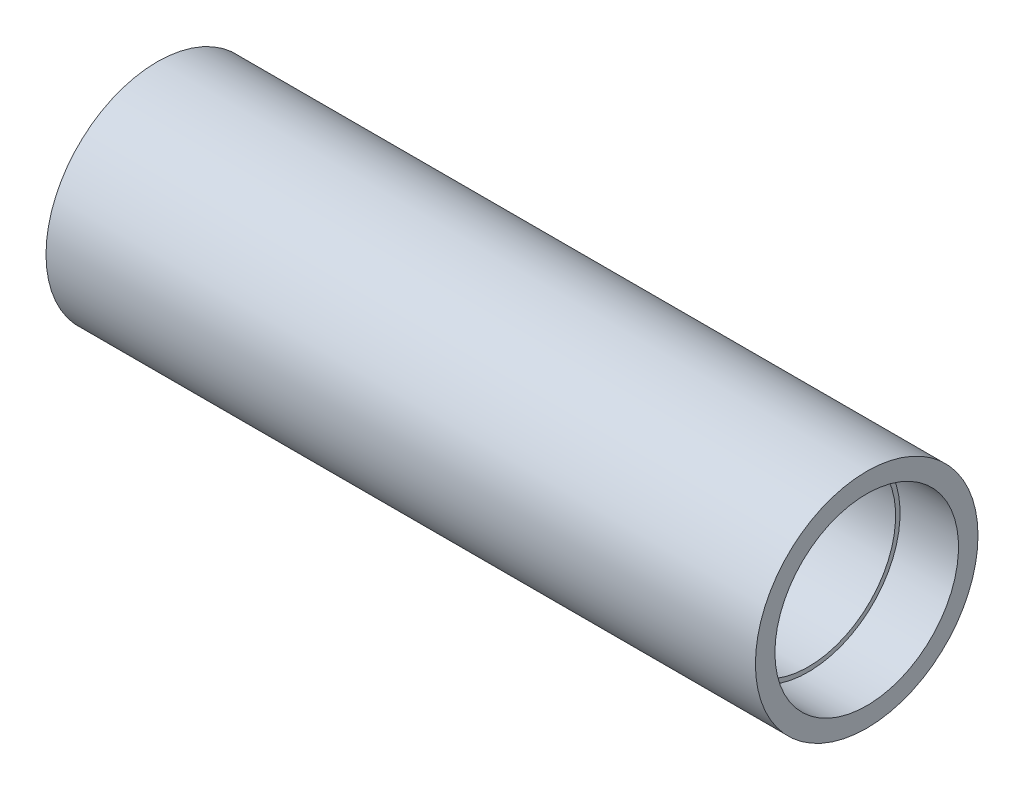
SolidWorks part; units mm, degrees
ref_plane "Front Plane" through (0, 0, 0) normal (0, 0, 1) x (1, 0, 0)
ref_plane "Top Plane" through (0, 0, 0) normal (0, 1, 0) x (1, 0, 0)
ref_plane "Right Plane" through (0, 0, 0) normal (1, 0, 0) x (0, 0, -1)
sketch "Sketch2" plane through (0, 0, 0) normal (0, 1, 0) x (1, 0, 0)
  line L4 (-42.5, 0) -> (42.5, 0) construction
  line L5 (0, 0) -> (0, 13.335) construction
  line L7 (42.5, 13.335) -> (-42.5, 13.335)
  line L8 (-42.5, 13.335) -> (-42.5, 11)
  line L9 (-42.5, 11) -> (-35.5, 11)
  line L10 (-35.5, 11) -> (-35.5, 10.4648)
  line L11 (-42.5, 0) -> (-42.5, 11) construction
  line L12 (42.5, 11) -> (35.5, 11)
  line L13 (-35.5, 10.4648) -> (35.5, 10.4648)
  line L14 (42.5, 13.335) -> (42.5, 11)
  line L15 (35.5, 11) -> (35.5, 10.4648)
  point P4 (0, 0)
  point P17 (0, 10.4648)
  dimension "D1" = 85
  dimension "D2" = 11
  dimension "D3" = 7
  dimension "D4" = 13.335
  dimension "D5" = 10.4648
revolve "Revolve1" add sketch "Sketch2" angle 360 about L4
ref_plane "Plane1" through (0, 0, 0) normal (1, 0, 0) x (0, 0, -1)
